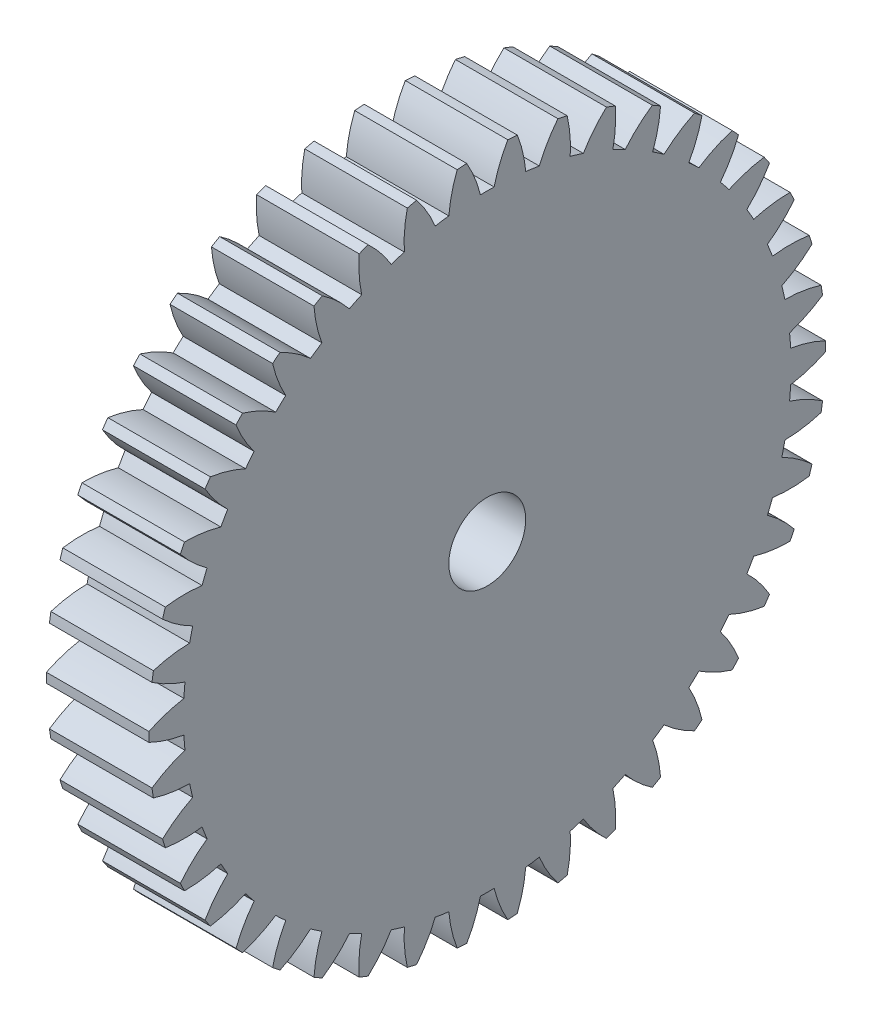
SolidWorks part; units mm, degrees
ref_plane "Plane1" through (0, 0, 0) normal (0, 0, 1) x (1, 0, 0)
ref_plane "Plane2" through (0, 0, 0) normal (0, 1, 0) x (1, 0, 0)
ref_plane "Plane3" through (0, 0, 0) normal (1, 0, 0) x (0, 0, -1)
sketch "HoldingSke" plane through (0, 0, 0) normal (0, 1, 0) x (1, 0, 0)
  line L0 (0, 0) -> (1.2386, -1.1152)
  line L1 (-15, 0) -> (100, 0) construction
  line L2 (0, 0) -> (-2.1039, 2.3779)
  line L3 (0, 0) -> (-11.863, 4.5341)
  line L4 (0, 0) -> (6.4178, 5.7786)
  line L5 (0, 0) -> (-46.8476, -17.4728)
  line L6 (0, 0) -> (-3.3159, -2.2372)
  line L7 (-2.1039, 2.3779) -> (8.6586, 51.2059)
  line L8 (-76.2, 54.61) -> (-75.7, 54.61)
  line L9 (-71.009, 38.7566) -> (-53.1078, 45.2721)
  line L10 (-76.2, 71.12) -> (104.1128, 71.12)
  line L11 (0, 0) -> (-4, 0)
  line L12 (-76.2, 101.6) -> (-76.177, 101.6)
  line L13 (24.9733, 27.94) -> (52.9518, 28.4284)
  line L14 (24.9733, 27.94) -> (24.9743, 27.94)
  line L15 (24.9733, 27.94) -> (100.4006, 29.5858)
  line L16 (-63.627, -0.6) -> (-12.827, -0.6)
  circle A0 centre (0, 0) radius 1.5
  circle A1 centre (0, 0) radius 11.849
  circle A2 centre (0, 0) radius 37.5
  circle A3 centre (0, 0) radius 1.5
  dimension "MHD" = 23.698
  dimension "Hub_dia" = 75
  dimension "Bore" = 3
  dimension "MBD" = 3
  dimension "Num_teeth" = 42
  dimension "Pitch" = 1.6667
  dimension "Overall_len" = 50
  dimension "Show_teeth" = 42
  dimension "Thickness" = 4
  dimension "OAL" = 50.0001
  dimension "T_dim" = 0.5
  dimension "Ap" = 20
  dimension "H" = 19.05
  dimension "Pitch_radius" = 180.3128
  dimension "Width" = 4
  dimension "Backlash" = 0.023
  dimension "Addendum_fac" = 1
  dimension "Dedendum_fac" = 1.25
  dimension "Clearance_fac" = 0.25
  dimension "Dedendum_add" = 0.001
  dimension "Module" = 0.6
sketch "BasProSke" plane through (0, 0, 0) normal (0, 1, 0) x (1, 0, 0)
  line L0 (-10, 0) -> (60, 0) construction
  line L1 (0, 0) -> (0, 13.2)
  line L2 (0, 0) -> (4, 0)
  line L3 (4, 0) -> (4, 13.2)
  line L4 (4, 13.2) -> (0, 13.2)
  dimension "Thickness" = 4
  dimension "Diameter" = 26.4
revolve "Base-Revolve" add sketch "BasProSke" angle 360 about L0
sketch "TooCutSke" plane through (0, 0, 0) normal (1, 0, 0) x (0, 0, -1)
  line L1 (0, 0) -> (0, 107) construction
  line L2 (0, 0) -> (-0.5114, 12.5896) construction
  line L3 (0, 0) -> (-1.8821, 25.1148) construction
  line L4 (-0.5114, 12.5896) -> (-0.941, 12.5574) construction
  arc A0 (0.2679, 11.846) -> (-0.2679, 11.846) centre (0, 0) ccw
  arc A1 (0.8153, 13.2002) -> (-0.8153, 13.2002) centre (0, 0) ccw
  circle A2 centre (0, 0) radius 12.6 construction
  circle A3 centre (0, 0) radius 11.8401 construction
  arc A4 (-0.2679, 11.846) -> (-0.8153, 13.2002) centre (-5.1649, 10.6542) ccw
  arc A5 (0.8153, 13.2002) -> (0.2679, 11.846) centre (5.1649, 10.6542) ccw
  dimension "Root_dia" = 23.698
  dimension "Overcut_dia" = 26.4508
  dimension "Pitch_dia" = 25.2
  dimension "Base_dia" = 23.6803
  dimension "Flank_rad" = 5.04
  dimension "Half_ang" = 4.286
  dimension "Half_CT" = 0.4309
extrude "ToothCut" cut sketch "TooCutSke" along normal through all
fillet "Breaks" [suppressed] radius 0.012
fillet "RootFillets" [suppressed] radius 0.151
pattern_circular "TeethCuts" count 42 every 8.571 about axis through (-10, 0, 0) along (1, 0, 0) of "ToothCut", "RootFillets", "Breaks"
sketch "HubNeaOneSke" plane through (0, 0, 0) normal (-1, 0, 0) x (0, 0, 1)
  circle A0 centre (0, 0) radius 11.849
  dimension "Diameter" = 23.698
extrude "HubNearOne" [suppressed] add sketch "HubNeaOneSke" along normal blind 46.0001
sketch "HubNeaBotSke" plane through (0, 0, 0) normal (-1, 0, 0) x (0, 0, 1)
  circle A0 centre (0, 0) radius 11.849
  dimension "Diameter" = 23.698
extrude "HubNearBoth" [suppressed] add sketch "HubNeaBotSke" along normal blind 23
ref_plane "FarPln" through (4, 0, 0) normal (1, 0, 0) x (0, 0, -1)
sketch "HubFarSke" plane through (4, 0, 0) normal (1, 0, 0) x (0, 0, -1)
  circle A0 centre (0, 0) radius 11.849
  dimension "Diameter" = 23.698
extrude "HubFar" [suppressed] add sketch "HubFarSke" along normal blind 23
sketch "BorSke" plane through (0, 0, 0) normal (1, 0, 0) x (0, 0, -1)
  circle A0 centre (0, 0) radius 1.5
  dimension "Diameter" = 3
extrude "Bore" cut sketch "BorSke" along normal mid plane 100.0001
sketch "KeySke" plane through (0, 0, 0) normal (1, 0, 0) x (0, 0, -1)
  line L0 (-0.6, 0) -> (-0.6, 2)
  line L1 (-0.6, 2) -> (0.6, 2)
  line L2 (0.6, 2) -> (0.6, 0)
  line L3 (0, 0) -> (0, 34) construction
  line L4 (-0.6, 0) -> (0.6, 0)
  dimension "Offset" = 2
  dimension "Width" = 1.2
extrude "Keyway" [suppressed] cut sketch "KeySke" along normal mid plane 100.0001
pattern_circular "Keyway2" [suppressed] count 2 every 90 about axis through (-10, 0, 0) along (1, 0, 0)
equation "' \"Module@HoldingSke\" = 6.35"
equation "' \"Num_teeth@HoldingSke\" = 12"
equation "' \"Ap@HoldingSke\" =  20"
equation "' \"Ap@HoldingSke\" = 20"
equation "' \"Width@HoldingSke\" = 0.5 * 25.4"
equation "' \"Hub_dia@HoldingSke\"= 1 * 25.4"
equation "' \"Hub_dia@HoldingSke\" = 1 * 25.4"
equation "' \"Overall_len@HoldingSke\" = 1.0 * 25.4"
equation "' \"Bore@HoldingSke\" = 0.75 * 25.4"
equation "' \"T_dim@HoldingSke\" = 0.1 * 25.4"
equation "' \"Width@KeySke\" = 0.25 * 25.4"
equation "' \"Show_teeth@HoldingSke\" = 13"
equation "' \"Backlash@HoldingSke\" = 0.009 * 25.4"
equation "' \"Addendum_fac@HoldingSke\" = 1.0"
equation "' \"Dedendum_fac@HoldingSke\" = 1.25"
equation "' \"Dedendum_add@HoldingSke\" = 0.00005 * 25.4"
equation "' \"Clearance_fac@HoldingSke\" = 0.25"
equation "\"Pitch@HoldingSke\" = 1 / \"Module@HoldingSke\""
equation "\"Overcut_dia@TooCutSke\" = (\"Num_teeth@HoldingSke\" + 2 * \"Addendum_fac@HoldingSke\") / \"Pitch@HoldingSke\" + 0.002 * 25.4"
equation "\"Pitch_dia@TooCutSke\" = \"Num_teeth@HoldingSke\" / \"Pitch@HoldingSke\""
equation "\"Base_dia@TooCutSke\" = \"Num_teeth@HoldingSke\" / \"Pitch@HoldingSke\" * cos((\"Ap@HoldingSke\"  * 3.14159265 / 180))"
equation "\"Root_dia@TooCutSke\" = (\"Num_teeth@HoldingSke\" + 2) / \"Pitch@HoldingSke\" - 2 * (\"Addendum_fac@HoldingSke\" + \"Dedendum_fac@HoldingSke\") / \"Pitch@HoldingSke\" - \"Dedendum_add@HoldingSke\" * 2"
equation "\"Half_ang@TooCutSke\" = 180 / \"Num_teeth@HoldingSke\""
equation "\"Half_CT@TooCutSke\" = \"Num_teeth@HoldingSke\" / \"Pitch@HoldingSke\" * sin((3.14159265 / 2 / \"Num_teeth@HoldingSke\")) / 2 - 7 * \"Backlash@HoldingSke\" / 4"
equation "\"Flank_rad@TooCutSke\" = \"Num_teeth@HoldingSke\" / \"Pitch@HoldingSke\" / 5"
equation "\"Radius@RootFillets\" = \"Clearance_fac@HoldingSke\" / \"Pitch@HoldingSke\" + \"Dedendum_add@HoldingSke\""
equation "\"Break_rad@Breaks\" = 0.02 / \"Pitch@HoldingSke\""
equation "\"Thickness@HoldingSke\" = \"Width@HoldingSke\""
equation "\"OAL@HoldingSke\" = \"Thickness@HoldingSke\""
equation "\"MHD@HoldingSke\" = (\"Num_teeth@HoldingSke\" + 2) / \"Pitch@HoldingSke\" - 2 * (\"Addendum_fac@HoldingSke\" + \"Dedendum_fac@HoldingSke\")  / \"Pitch@HoldingSke\" - \"Dedendum_add@HoldingSke\" * 2"
equation "\"MBD@HoldingSke\" = (\"Num_teeth@HoldingSke\" + 2) / \"Pitch@HoldingSke\" - 2 * (\"Addendum_fac@HoldingSke\" + \"Dedendum_fac@HoldingSke\")  / \"Pitch@HoldingSke\" - \"Dedendum_add@HoldingSke\" * 2 - 0.002 * 25.4"
equation "\"MHD@HoldingSke\" = ((sgn( \"MHD@HoldingSke\" - \"Hub_dia@HoldingSke\" )-1)*( \"MHD@HoldingSke\" - \"Hub_dia@HoldingSke\" ))/-2+ \"Hub_dia@HoldingSke\""
equation "\"MBD@HoldingSke\" = ((sgn( \"MBD@HoldingSke\" - \"Bore@HoldingSke\" )-1)*( \"MBD@HoldingSke\" - \"Bore@HoldingSke\" ))/-2+ \"Bore@HoldingSke\""
equation "\"OAL@HoldingSke\" = ((sgn( \"OAL@HoldingSke\" - \"Overall_len@HoldingSke\" )+1)*( \"OAL@HoldingSke\" - \"Overall_len@HoldingSke\" ))/2 + \"Overall_len@HoldingSke\" + 0.000002 * 25.4"
equation "\"Num_teeth@TeethCuts\" = int( \"Show_teeth@HoldingSke\" ) + 1"
equation "\"Num_teeth@TeethCuts\" = ((sgn( \"Num_teeth@TeethCuts\" - \"Num_teeth@HoldingSke\" )-1)*( \"Num_teeth@TeethCuts\" - \"Num_teeth@HoldingSke\" ))/-2+ \"Num_teeth@HoldingSke\""
equation "\"Num_teeth@TeethCuts\" = ((sgn( \"Num_teeth@TeethCuts\" - 2.0)+1)*( \"Num_teeth@TeethCuts\" - 2.0))/2 +2.0"
equation "\"Angle@TeethCuts\" = 360.0 / \"Num_teeth@HoldingSke\""
equation "\"Diameter@BasProSke\" = (\"Num_teeth@HoldingSke\" + 2 * \"Addendum_fac@HoldingSke\") / \"Pitch@HoldingSke\""
equation "\"Thickness@BasProSke\"  = \"Thickness@HoldingSke\""
equation "' \"Fillet_rad@BasProSke\" =  \"Thickness@HoldingSke\" * 0.05"
equation "' \"Fillet_rad@BasProSke\" = \"Thickness@HoldingSke\" * 0.05"
equation "\"MHD@HoldingSke\" = ((sgn( \"MHD@HoldingSke\" - \"Root_dia@TooCutSke\" )-1)*( \"MHD@HoldingSke\" - \"Root_dia@TooCutSke\" ))/-2+ \"Root_dia@TooCutSke\""
equation "\"Diameter@HubNeaOneSke\" = \"MHD@HoldingSke\""
equation "\"Length@HubNearOne\" = \"OAL@HoldingSke\" - \"Thickness@BasProSke\""
equation "\"Diameter@HubNeaBotSke\" = \"MHD@HoldingSke\""
equation "\"Length@HubNearBoth\" = ( \"OAL@HoldingSke\" - \"Thickness@BasProSke\" ) / 2.0"
equation "\"Thickness@FarPln\" = \"Thickness@BasProSke\""
equation "\"Diameter@HubFarSke\" = \"MHD@HoldingSke\""
equation "\"Length@HubFar\" = ( \"OAL@HoldingSke\" - \"Thickness@BasProSke\" ) / 2.0"
equation "\"Diameter@BorSke\" = \"MBD@HoldingSke\""
equation "\"D1@Bore\" = \"OAL@HoldingSke\" * 2.0"
equation "\"D1@Keyway\" = \"OAL@HoldingSke\" * 2.0"
equation "\"Offset@KeySke\" = \"T_dim@HoldingSke\" + \"MBD@HoldingSke\" / 2.0"
